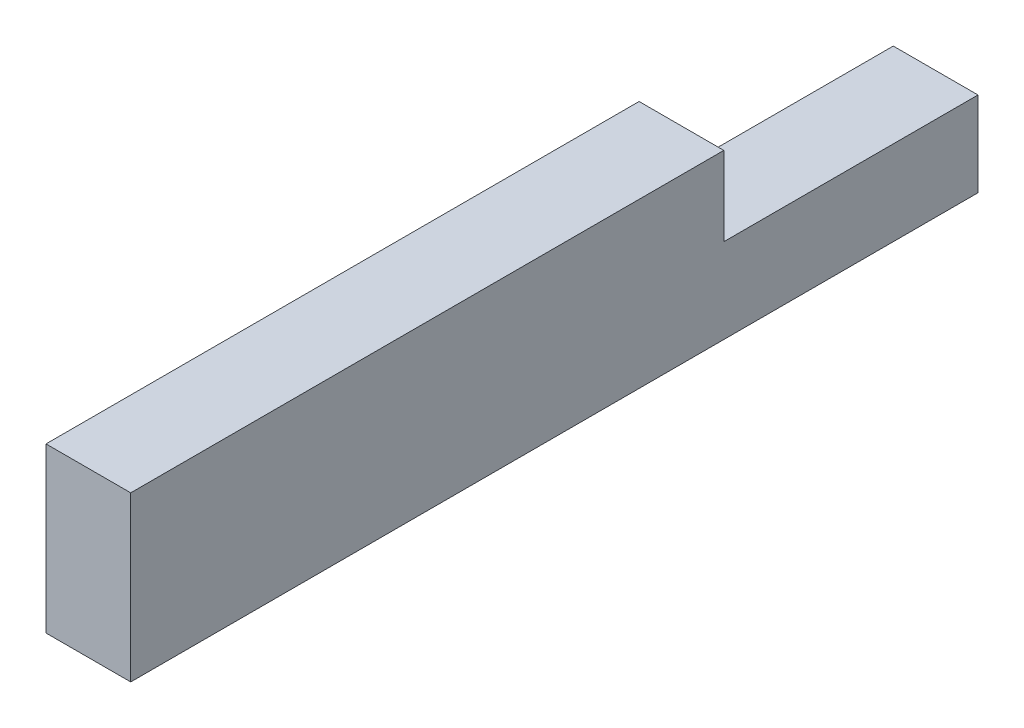
SolidWorks part; units mm, degrees
ref_plane "Front" through (0, 0, 0) normal (0, 0, 1) x (1, 0, 0)
ref_plane "Top" through (0, 0, 0) normal (0, 1, 0) x (1, 0, 0)
ref_plane "Right" through (0, 0, 0) normal (1, 0, 0) x (0, 0, -1)
sketch "ｽｹｯﾁ1" plane through (0, 0, 0) normal (0, 0, 1) x (1, 0, 0)
  line L1 (1.5, -1.5) -> (-1.5, -1.5)
  line L2 (1.5, -1.5) -> (1.5, 1.5)
  line L3 (1.5, 1.5) -> (-1.5, 1.5)
  line L4 (-1.5, -1.5) -> (-1.5, 1.5)
  line L5 (1.5, -1.5) -> (-1.5, 1.5) construction
  line L6 (1.5, 1.5) -> (-1.5, -1.5) construction
  point P0 (0, 0)
  dimension "D1" = 3
extrude "ﾎﾞｽ - 押し出し1" add sketch "ｽｹｯﾁ1" along normal blind 30
sketch "ｽｹｯﾁ2" plane through (0, 1.5, 0) normal (0, 1, 0) x (1, 0, 0)
  line L0 (1.5, -30) -> (1.5, 0) construction
  line L1 (-1.5, -30) -> (1.5, -30)
  line L2 (-1.5, -30) -> (-1.5, -9)
  line L3 (-1.5, -9) -> (1.5, -9)
  line L4 (1.5, -30) -> (1.5, -9)
  line L5 (1.5, 0) -> (-1.5, 0) construction
  dimension "D1" = 9
extrude "ﾎﾞｽ - 押し出し2" add sketch "ｽｹｯﾁ2" along normal blind 2.8
sketch "ｽｹｯﾁ3" plane through (0, 4.3, 0) normal (0, 1, 0) x (1, 0, 0)
  line L0 (-1.5, -30) -> (1.5, -30) construction
  line L1 (1.5, -9) -> (-3.5, -9)
  line L2 (1.5, -9) -> (1.5, -30)
  line L3 (1.5, -30) -> (-3.5, -30)
  line L4 (-3.5, -9) -> (-3.5, -30)
  dimension "D1" = 5
extrude "ﾎﾞｽ - 押し出し3" [suppressed] add sketch "ｽｹｯﾁ3" along normal blind 3
sketch "ｽｹｯﾁ4" [suppressed] plane through (0, 7.3, 0) normal (0, 1, 0) x (1, 0, 0)
  line L0 (-3.5, -28.425) -> (0.25, -27.0601)
  line L1 (-3.5, -9) -> (-3.5, -30) construction
  line L2 (0.25, -27.0601) -> (0.25, -26.07)
  line L3 (0.25, -26.07) -> (-3.5, -24.7051)
  line L4 (0.25, -26.5651) -> (-3.5, -26.5651) construction
  line L5 (-1.625, -25.3876) -> (-1.625, -27.7426) construction
  line L6 (-3.5, -30) -> (1.5, -30) construction
  dimension "D1" = 3.75
  dimension "D2" = 1.875
  dimension "D3" = 2.355
  dimension "D4" = 70
  dimension "D5" = 1.575
extrude "ｶｯﾄ - 押し出し1" [suppressed] cut sketch "ｽｹｯﾁ4" against normal blind 3 and the other way through all
pattern_linear "直線ﾊﾟﾀｰﾝ2" [suppressed] count 4 spacing 4.71
fillet "ﾌｨﾚｯﾄ1" [suppressed] radius 0.25
